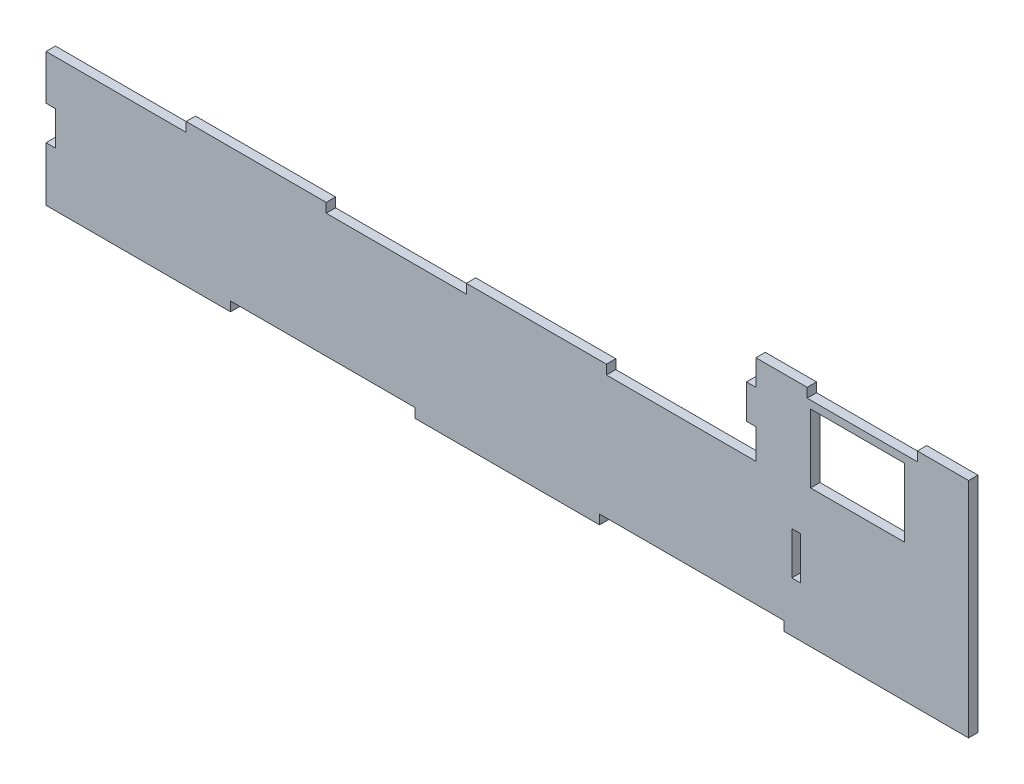
SolidWorks part; units mm, degrees
ref_plane "Alzado" through (0, 0, 0) normal (0, 0, 1) x (1, 0, 0)
ref_plane "Planta" through (0, 0, 0) normal (0, 1, 0) x (1, 0, 0)
ref_plane "Vista lateral" through (0, 0, 0) normal (1, 0, 0) x (0, 0, -1)
sketch "Croquis1" plane through (0, 0, 0) normal (0, 0, 1) x (1, 0, 0)
  line L0 (-71.9836, 36.1082) -> (-71.9836, 9.8582)
  line L1 (174.0164, 41.6082) -> (256.0164, 41.6082)
  line L2 (343.5164, 88.6082) -> (373.5164, 88.6082)
  line L3 (-71.9836, -41.8918) -> (36.0164, -41.8918)
  line L4 (468.0164, 88.6082) -> (468.0164, -41.8918)
  line L5 (36.0164, -41.8918) -> (36.0164, -36.3918)
  line L6 (36.0164, -36.3918) -> (144.0164, -36.3918)
  line L7 (144.0164, -36.3918) -> (144.0164, -41.8918)
  line L8 (144.0164, -41.8918) -> (252.0164, -41.8918)
  line L9 (252.0164, -41.8918) -> (252.0164, -36.3918)
  line L10 (252.0164, -36.3918) -> (360.0164, -36.3918)
  line L11 (360.0164, -36.3918) -> (360.0164, -41.8918)
  line L12 (360.0164, -41.8918) -> (468.0164, -41.8918)
  line L13 (373.5164, 88.6082) -> (373.5164, 83.1082)
  line L14 (343.5164, 88.6082) -> (343.5164, 73.6082)
  line L15 (10.0164, 36.1082) -> (10.0164, 41.6082)
  line L16 (92.0164, 36.1082) -> (174.0164, 36.1082)
  line L17 (256.0164, 41.6082) -> (256.0164, 36.1082)
  line L18 (-71.9836, 36.1082) -> (10.0164, 36.1082)
  line L19 (375.5164, 78.6082) -> (430.5164, 78.6082)
  line L20 (92.0164, 41.6082) -> (92.0164, 36.1082)
  line L21 (10.0164, 41.6082) -> (92.0164, 41.6082)
  line L22 (375.5164, 78.6082) -> (375.5164, 38.6082)
  line L23 (174.0164, 36.1082) -> (174.0164, 41.6082)
  line L24 (375.5164, 38.6082) -> (430.5164, 38.6082)
  line L25 (144.0164, -36.3918) -> (252.0164, -36.3918) construction
  line L26 (360.0164, -36.3918) -> (468.0164, -36.3918) construction
  line L27 (360.0164, -41.8918) -> (252.0164, -41.8918) construction
  line L28 (144.0164, -41.8918) -> (36.0164, -41.8918) construction
  line L29 (430.5164, 78.6082) -> (430.5164, 38.6082)
  line L30 (364.5164, -12.5) -> (364.5164, 12.5)
  line L31 (364.5164, -12.5) -> (369.5164, -12.5)
  line L32 (369.5164, -12.5) -> (369.5164, 12.5)
  line L33 (364.5164, 12.5) -> (369.5164, 12.5)
  line L34 (-71.9836, -10.1418) -> (-71.9836, -41.8918)
  line L35 (-71.9836, 9.8582) -> (-66.4836, 9.8582)
  line L36 (256.0164, 36.1082) -> (338.0164, 36.1082)
  line L37 (-71.9836, -10.1418) -> (-66.4836, -10.1418)
  line L38 (-66.4836, 9.8582) -> (-66.4836, -10.1418)
  line L39 (364.5164, -35.8918) -> (364.5164, 33.1082) construction
  line L40 (364.5164, -35.8918) -> (441.5164, -35.8918) construction
  line L41 (441.5164, -35.8918) -> (441.5164, 33.1082) construction
  line L42 (364.5164, 33.1082) -> (441.5164, 33.1082) construction
  line L43 (373.5164, 83.1082) -> (438.0164, 83.1082)
  line L44 (438.0164, 83.1082) -> (438.0164, 88.6082)
  line L45 (343.5164, 53.6082) -> (343.5164, 36.1082)
  line L46 (343.5164, 36.1082) -> (338.0164, 36.1082)
  line L47 (438.0164, 88.6082) -> (468.0164, 88.6082)
  line L48 (438.0164, 88.6082) -> (373.5164, 88.6082) construction
  line L56 (338.0164, 73.6082) -> (343.5164, 73.6082)
  line L57 (338.0164, 73.6082) -> (338.0164, 53.6082)
  line L58 (338.0164, 53.6082) -> (343.5164, 53.6082)
  dimension "D1" = 78
  dimension "D2" = 540
  dimension "D3" = 5.5
  dimension "D4" = 125
  dimension "D5" = 410
  dimension "D6" = 26.25
  dimension "D7" = 26.25
  dimension "D8" = 5.5
  dimension "D9" = 124.5
extrude "Saliente-Extruir1" add sketch "Croquis1" along normal blind 5.5
